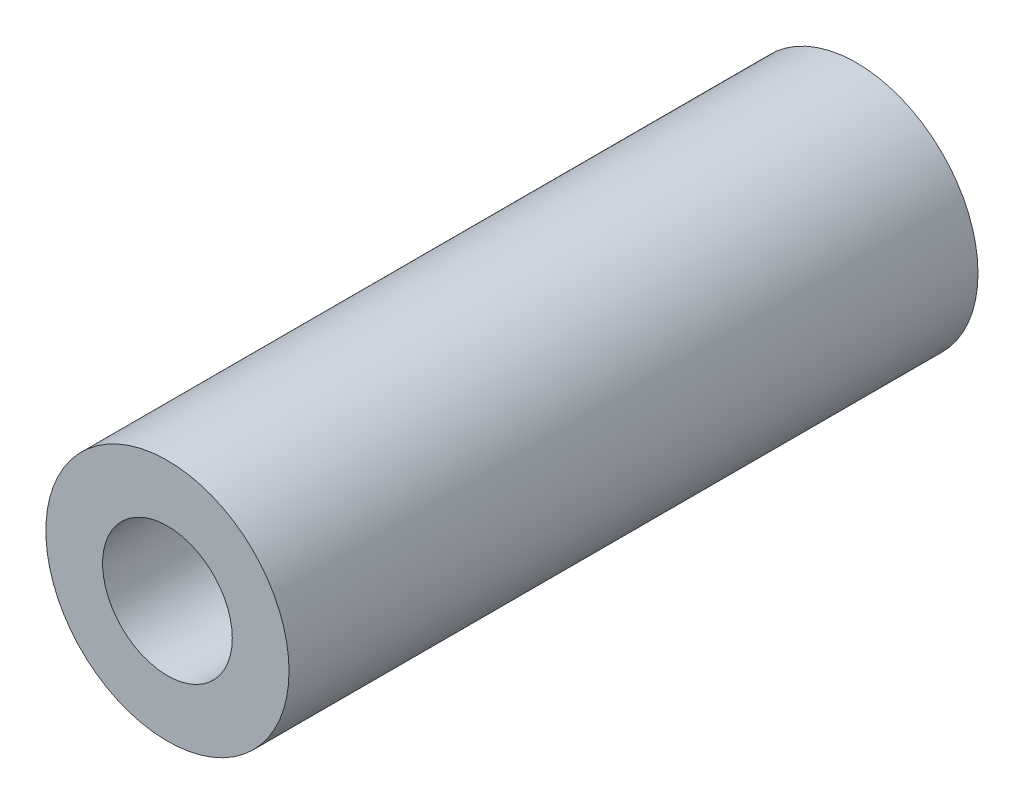
SolidWorks part; units mm, degrees
ref_plane "Front Plane" through (0, 0, 0) normal (0, 0, 1) x (1, 0, 0)
ref_plane "Top Plane" through (0, 0, 0) normal (0, 1, 0) x (1, 0, 0)
ref_plane "Right Plane" through (0, 0, 0) normal (1, 0, 0) x (0, 0, -1)
sketch "Sketch1" plane through (0, 0, 0) normal (0, 0, 1) x (1, 0, 0)
  circle A0 centre (0, 0) radius 3
  circle A1 centre (0, 0) radius 1.6
  dimension "OD" = 6
  dimension "ID" = 3.2
extrude "Extrude1" add sketch "Sketch1" along normal mid plane 17
sketch "Sketch2" plane through (0, 0, 0) normal (1, 0, 0) x (0, 0, -1)
  line L0 (-8.5, -1.6) -> (8.5, -1.6) construction
  line L3 (8.5, 1.6) -> (-8.5, 1.6) construction
  line L5 (-8.5, -1.6) -> (8.5, -1.6)
  line L6 (8.5, 1.6) -> (-8.5, 1.6)
sketch "Sketch4" plane through (0, 0, 8.5) normal (0, 0, 1) x (1, 0, 0)
  line L0 (0, 0) -> (-1.1314, 1.1314)
  line L1 (0, -2.475) -> (0, 2.475) construction
  circle A0 centre (0, 0) radius 1.6 construction
  dimension "D1" = 45
